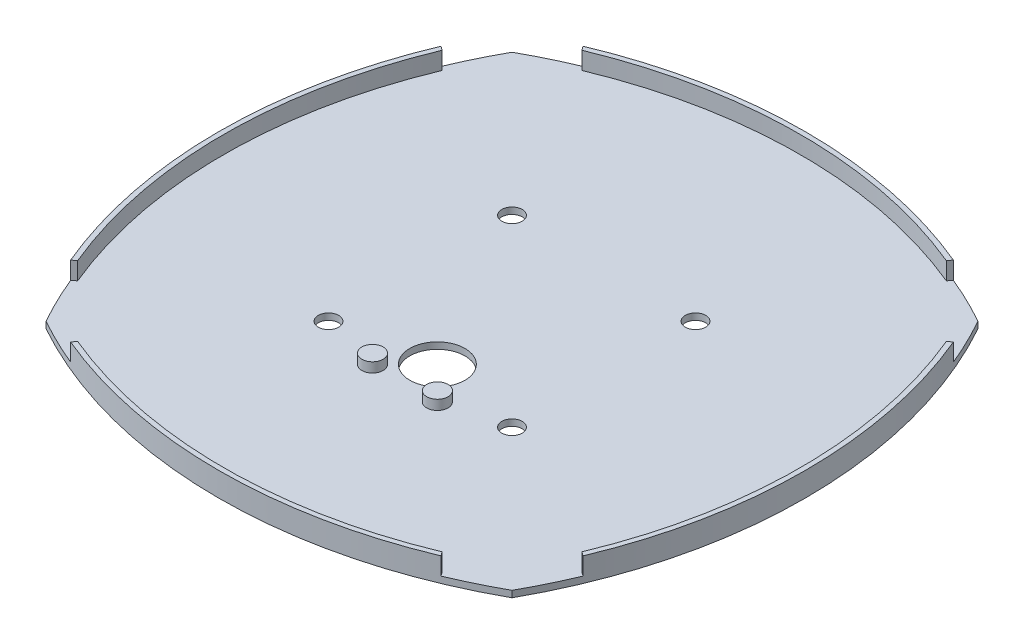
SolidWorks part; units mm, degrees
ref_plane "Front Plane" through (0, 0, 0) normal (0, 0, 1) x (1, 0, 0)
ref_plane "Top Plane" through (0, 0, 0) normal (0, 1, 0) x (1, 0, 0)
ref_plane "Right Plane" through (0, 0, 0) normal (1, 0, 0) x (0, 0, -1)
sketch "Sketch1" plane through (0, 0, 0) normal (0, 1, 0) x (1, 0, 0)
  line L0 (175.429, 389.4302) -> (225.429, 389.4742) construction
  dimension "D1" = 50
sketch "Sketch3" plane through (0, 0, 0) normal (0, 1, 0) x (1, 0, 0)
  line L2 (199.3319, -52.9004) -> (358.0133, -52.9004) construction
  line L3 (199.3319, -52.9004) -> (199.3319, 49.5555) construction
  arc A5 (130.4554, 15.9761) -> (130.4554, -121.7769) centre (256.8431, -52.9004) ccw construction
  arc A6 (268.2084, 15.9761) -> (130.4554, 15.9761) centre (199.3319, -110.4116) ccw construction
  arc A7 (268.2084, -121.7769) -> (268.2084, 15.9761) centre (141.8208, -52.9004) ccw construction
  arc A9 (130.4554, -121.7769) -> (268.2084, -121.7769) centre (199.3319, 4.6107) ccw construction
  arc A12 (271.1535, 18.9212) -> (127.5103, 18.9212) centre (199.3319, -110.4116) ccw
  arc A14 (127.5103, 18.9212) -> (127.5103, -124.722) centre (256.8431, -52.9004) ccw
  arc A15 (127.5103, -124.722) -> (271.1535, -124.722) centre (199.3319, 4.6107) ccw
  arc A16 (271.1535, -124.722) -> (271.1535, 18.9212) centre (141.8208, -52.9004) ccw
  point P0 (199.3319, -52.9004)
  point P15 (199.3319, -52.9004)
  dimension "D1" = 4
extrude "Boss-Extrude1" add sketch "Sketch3" along normal blind 2
sketch "Sketch5" plane through (0, 2, 0) normal (0, 1, 0) x (1, 0, 0)
  line L0 (141.8208, -52.9004) -> (256.8431, -52.9004) construction
  line L1 (199.3319, 4.6107) -> (199.3319, -110.4116) construction
  line L2 (121.6116, -109.0803) -> (120.3642, -109.9865)
  line L3 (143.1521, -130.6208) -> (142.2458, -131.8681)
  line L4 (277.0523, 3.2794) -> (278.2996, 4.1857)
  line L5 (255.5118, 24.8199) -> (256.418, 26.0673)
  line L6 (277.0523, -109.0803) -> (278.2996, -109.9865)
  line L7 (255.5118, -130.6208) -> (256.418, -131.8681)
  line L8 (121.6125, 3.2817) -> (120.3652, 4.1879)
  line L9 (143.1498, 24.819) -> (142.2436, 26.0663)
  line L10 (110.4063, 20.1528) -> (110.4063, -83.3423) construction
  line L11 (288.2576, 27.2093) -> (288.2576, -79.0531) construction
  line L12 (35.0838, 36.0252) -> (347.5932, 36.0252) construction
  line L13 (32.3242, -141.8261) -> (353.5329, -141.8261) construction
  arc A8 (128.614, -123.6184) -> (270.0499, -123.6184) centre (199.3319, 4.6107) ccw
  arc A9 (270.0499, -123.6184) -> (270.0499, 17.8175) centre (141.8208, -52.9004) ccw
  arc A10 (270.0499, 17.8175) -> (128.614, 17.8175) centre (199.3319, -110.4116) ccw
  arc A11 (128.614, 17.8175) -> (128.614, -123.6184) centre (256.8431, -52.9004) ccw
  arc A12 (143.1521, -130.6208) -> (255.5118, -130.6208) centre (199.3319, 4.6107) ccw
  arc A13 (277.0523, -109.0803) -> (277.0523, 3.2794) centre (141.8208, -52.9004) ccw
  arc A14 (255.5118, 24.8199) -> (143.1498, 24.819) centre (199.3319, -110.4116) ccw
  arc A15 (121.6125, 3.2817) -> (121.6116, -109.0803) centre (256.8431, -52.9004) ccw
  arc A21 (271.1535, 18.9212) -> (127.5103, 18.9212) centre (199.3319, -110.4116) ccw
  arc A22 (271.1535, -124.722) -> (271.1535, 18.9212) centre (141.8208, -52.9004) ccw
  arc A23 (127.5103, -124.722) -> (271.1535, -124.722) centre (199.3319, 4.6107) ccw
  arc A24 (127.5103, 18.9212) -> (127.5103, -124.722) centre (256.8431, -52.9004) ccw
  arc A25 (256.418, 26.0673) -> (142.2436, 26.0663) centre (199.3319, -110.4116) ccw
  arc A26 (278.2996, -109.9865) -> (278.2996, 4.1857) centre (141.8208, -52.9004) ccw
  arc A27 (142.2458, -131.8681) -> (256.418, -131.8681) centre (199.3319, 4.6107) ccw
  arc A28 (120.3652, 4.1879) -> (120.3642, -109.9865) centre (256.8431, -52.9004) ccw
  dimension "D2" = 36
  dimension "D3" = 36
  dimension "D4" = 36
  dimension "D5" = 36
  dimension "D6" = 36
  dimension "D7" = 36
  dimension "D8" = 36
  dimension "D9" = 36
  dimension "D1" = 1.5
  dimension "D10" = 0
extrude "Boss-Extrude2" add sketch "Sketch5" along normal blind 5.4
sketch "Sketch6" plane through (0, 2, 0) normal (0, 1, 0) x (1, 0, 0)
  line L0 (127.5103, -124.722) -> (271.1535, 18.9212) construction
  line L1 (127.5103, 18.9212) -> (271.1535, -124.722) construction
  line L2 (199.3319, -54.185) -> (199.3319, 43.8674) construction
  circle A1 centre (199.3319, -84.7202) radius 22.5
  point P12 (199.3319, -52.9004)
  dimension "D1" = 45
ref_plane "Plane1" through (0, 60, 0) normal (0, 1, 0) x (1, 0, 0)
sketch "Sketch11" plane through (0, 2, 0) normal (0, 1, 0) x (1, 0, 0)
  line L0 (127.5103, -124.722) -> (271.1535, 18.9212) construction
  line L1 (127.5103, 18.9212) -> (271.1535, -124.722) construction
  line L2 (199.3319, -50.7415) -> (199.3319, 48.5237) construction
  line L3 (199.3319, -52.9004) -> (293.7423, -52.9004) construction
  circle A0 centre (171.0477, -24.6162) radius 3.15
  circle A1 centre (227.6162, -24.6162) radius 3.15
  circle A2 centre (227.6162, -81.1847) radius 3.15
  circle A3 centre (171.0477, -81.1847) radius 3.15
  circle A4 centre (199.3319, -75.9004) radius 8.5
  point P11 (199.3319, -52.9004)
  point P24 (199.3319, -52.9004)
  dimension "D2" = 6.3
  dimension "D4" = 17
  dimension "D3" = 40
  dimension "D5" = 23
  dimension "D1" = 4
extrude "Cut-Extrude2" cut sketch "Sketch11" against normal through all both and the other way through all
sketch "Sketch13" plane through (0, 2, 0) normal (0, 1, 0) x (1, 0, 0)
  line L0 (199.3319, -74.6137) -> (199.3319, -39.6509) construction
  line L1 (199.3319, -75.9004) -> (212.0826, -75.9004) construction
  circle A5 centre (189.3319, -85.9004) radius 3.2895
  circle A6 centre (209.3319, -85.9004) radius 3.2895
  point P1 (199.3319, -75.9004)
  point P14 (199.3319, -75.9004)
  dimension "D1" = 10
  dimension "D2" = 10
extrude "Boss-Extrude3" add sketch "Sketch13" along normal blind 3
sketch "Sketch7" plane through (0, 60, 0) normal (0, 1, 0) x (1, 0, 0)
  line L0 (199.3319, -200054.185) -> (199.3319, 200043.8674) construction
  circle A0 centre (199.3319, -97.9702) radius 9
  dimension "D1" = 18
loft "Loft1" [suppressed] add profiles "Sketch7", "Sketch6"
sketch "Sketch8" [suppressed] plane through (0, 2.5, 0) normal (0, 1, 0) x (1, 0, 0)
  line L0 (199.3319, -97.9702) -> (199.3319, -52.584) construction
  line L1 (127.5103, -124.722) -> (271.1535, 18.9212) construction
  line L2 (127.5103, 18.9212) -> (271.1535, -124.722) construction
  circle A4 centre (199.3319, -97.9702) radius 9 construction
  circle A5 centre (199.3319, -75.9004) radius 8.5
  point P0 (199.3319, -97.9702)
  point P10 (199.3319, -52.9004)
  dimension "D1" = 17
  dimension "D2" = 23
sketch "Sketch9" [suppressed] plane through (0, 60, 0) normal (0, 1, 0) x (1, 0, 0)
  circle A0 centre (199.3319, -97.9702) radius 6
  dimension "D1" = 12
loft "Cut-Loft1" [suppressed] cut profiles "Sketch9", "Sketch8"
